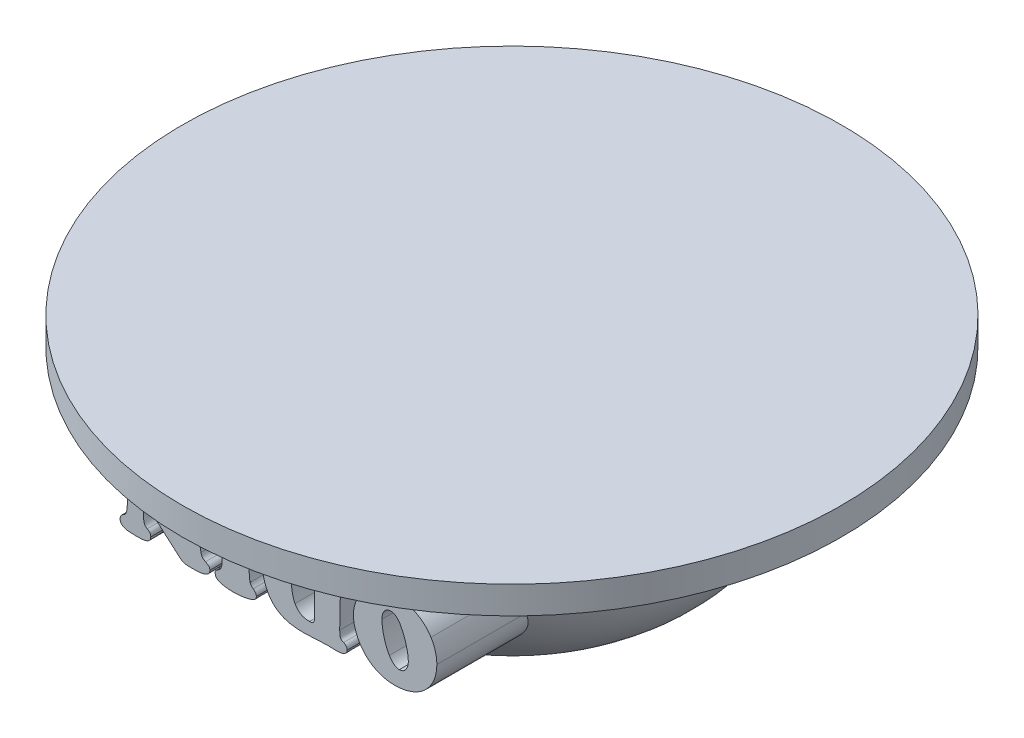
SolidWorks part; units mm, degrees
ref_plane "Plan de face" through (0, 0, 0) normal (0, 0, 1) x (1, 0, 0)
ref_plane "Plan de dessus" through (0, 0, 0) normal (0, 1, 0) x (1, 0, 0)
ref_plane "Plan de droite" through (0, 0, 0) normal (1, 0, 0) x (0, 0, -1)
sketch "Esquisse1" plane through (0, 0, 0) normal (0, 1, 0) x (1, 0, 0)
  circle A0 centre (0, 0) radius 16
extrude "Boss.-Extru.1" add sketch "Esquisse1" along normal blind 15 contours A0
fillet "Congé4" radius 10 1 edges at (0, 0, 16)
sketch "Esquisse5" plane through (0, 15, 0) normal (0, 1, 0) x (1, 0, 0)
  circle A0 centre (0, 0) radius 24
extrude "Boss.-Extru.4" add sketch "Esquisse5" against normal blind 2
sketch "Esquisse6" plane through (0, 0, 0) normal (0, 0, 1) x (1, 0, 0)
  text T0 "ODIN" font "Cooper Black" height in points 24
extrude "Boss.-Extru.5" add sketch "Esquisse6" along normal blind 17
